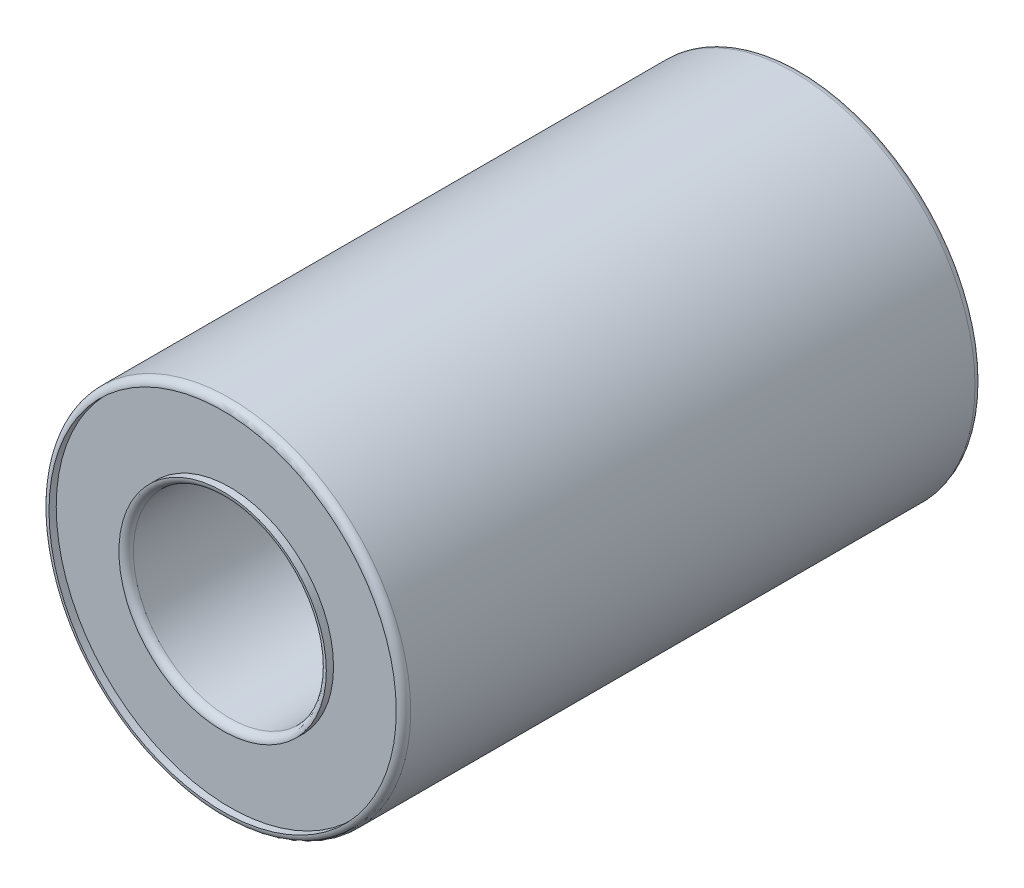
SolidWorks part; units mm, degrees
ref_plane "Front Plane" through (0, 0, 0) normal (0, 0, 1) x (1, 0, 0)
ref_plane "Top Plane" through (0, 0, 0) normal (0, 1, 0) x (1, 0, 0)
ref_plane "Right Plane" through (0, 0, 0) normal (1, 0, 0) x (0, 0, -1)
sketch "Sketch1" plane through (0, 0, 0) normal (0, 0, 1) x (1, 0, 0)
  circle A0 centre (0, 0) radius 7.5
  dimension "D1" = 15
extrude "Boss-Extrude1" add sketch "Sketch1" along normal blind 24
sketch "Sketch2" plane through (0, 0, 24) normal (0, 0, 1) x (1, 0, 0)
  circle A0 centre (0, 0) radius 4
  dimension "D1" = 8
extrude "Cut-Extrude1" cut sketch "Sketch2" against normal blind 24
fillet "Fillet2" radius 0.3 2 edges at (4, 0, 24) (4, 0, 0)
fillet "Fillet3" radius 0.3 2 edges at (7.5, 0, 0) (7.5, 0, 24)
sketch "Sketch3" plane through (0, 0, 0) normal (0, 0, -1) x (-1, 0, 0)
  circle A0 centre (0, 0) radius 4.3 construction
  circle A1 centre (0, 0) radius 7.2
  circle A2 centre (0, 0) radius 7.2
  circle A3 centre (0, 0) radius 4.3
  dimension "D1" = 0
extrude "Cut-Extrude2" cut sketch "Sketch3" against normal blind 0.3 contours A2 | A3
sketch "Sketch4" plane through (0, 0, 24) normal (0, 0, 1) x (1, 0, 0)
  circle A0 centre (0, 0) radius 4.3 construction
  circle A1 centre (0, 0) radius 7.2
  circle A2 centre (0, 0) radius 7.2
  circle A3 centre (0, 0) radius 4.3
  dimension "D1" = 0
extrude "Cut-Extrude4" cut sketch "Sketch4" against normal blind 0.3
